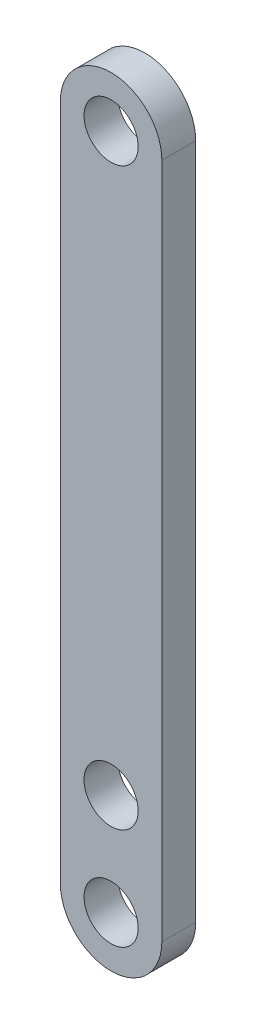
SolidWorks part; units mm, degrees
ref_plane "Piano frontale" through (0, 0, 0) normal (0, 0, 1) x (1, 0, 0)
ref_plane "Piano superiore" through (0, 0, 0) normal (0, 1, 0) x (1, 0, 0)
ref_plane "Piano destro" through (0, 0, 0) normal (1, 0, 0) x (0, 0, -1)
sketch "Schizzo1" plane through (0, 0, 0) normal (0, 0, 1) x (1, 0, 0)
  line L2 (-7.5, -50) -> (-7.5, 50)
  line L4 (7.5, -50) -> (7.5, 50)
  line L5 (-7.5, -50) -> (7.5, 50) construction
  line L6 (-7.5, 50) -> (7.5, -50) construction
  arc A0 (-7.5, 50) -> (7.5, 50) centre (0, 50) cw
  arc A1 (-7.5, -50) -> (7.5, -50) centre (0, -50) ccw
  circle A2 centre (0, 50) radius 4
  circle A3 centre (0, -35) radius 4
  circle A4 centre (0, -50) radius 4
  point P0 (0, 0)
  dimension "D2" = 7.5
  dimension "D3" = 8
  dimension "D1" = 15
  dimension "D4" = 100
extrude "Estrusione1" add sketch "Schizzo1" along normal blind 5
